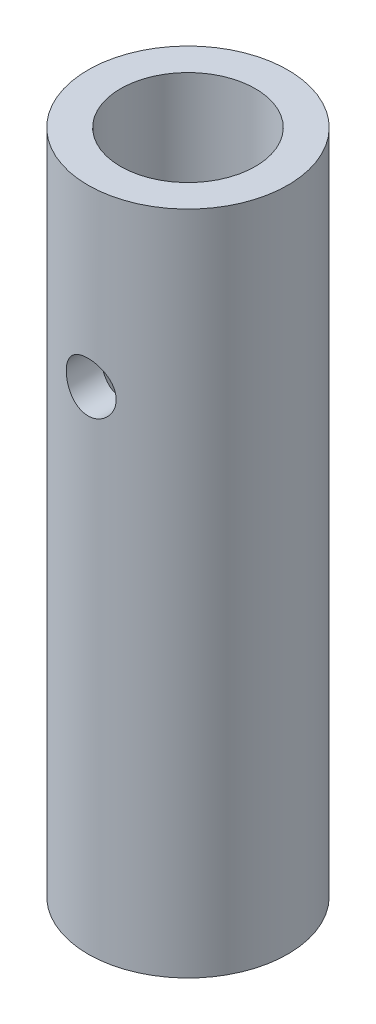
SolidWorks part; units mm, degrees
ref_plane "前视基准面" through (0, 0, 0) normal (0, 0, 1) x (1, 0, 0)
ref_plane "上视基准面" through (0, 0, 0) normal (0, 1, 0) x (1, 0, 0)
ref_plane "右视基准面" through (0, 0, 0) normal (1, 0, 0) x (0, 0, -1)
other "Configuration Table"
sketch "草图1" plane through (0, 0, 0) normal (0, 1, 0) x (1, 0, 0)
  circle A0 centre (0, 0) radius 4.05
  circle A1 centre (0, 0) radius 6
  dimension "D1" = 8.1
  dimension "D2" = 12
extrude "凸台-拉伸1" add sketch "草图1" along normal blind 40
sketch "草图2" plane through (0, 0, 0) normal (0, 0, 1) x (1, 0, 0)
  line L0 (0, 40) -> (0, 29.5)
  line L1 (6, 40) -> (-6, 40) construction
  circle A0 centre (0, 29.5) radius 1.5
  dimension "D2" = 3
  dimension "D1" = 10.5
extrude "切除-拉伸1" cut sketch "草图2" against normal through all both and the other way through all contours A0
